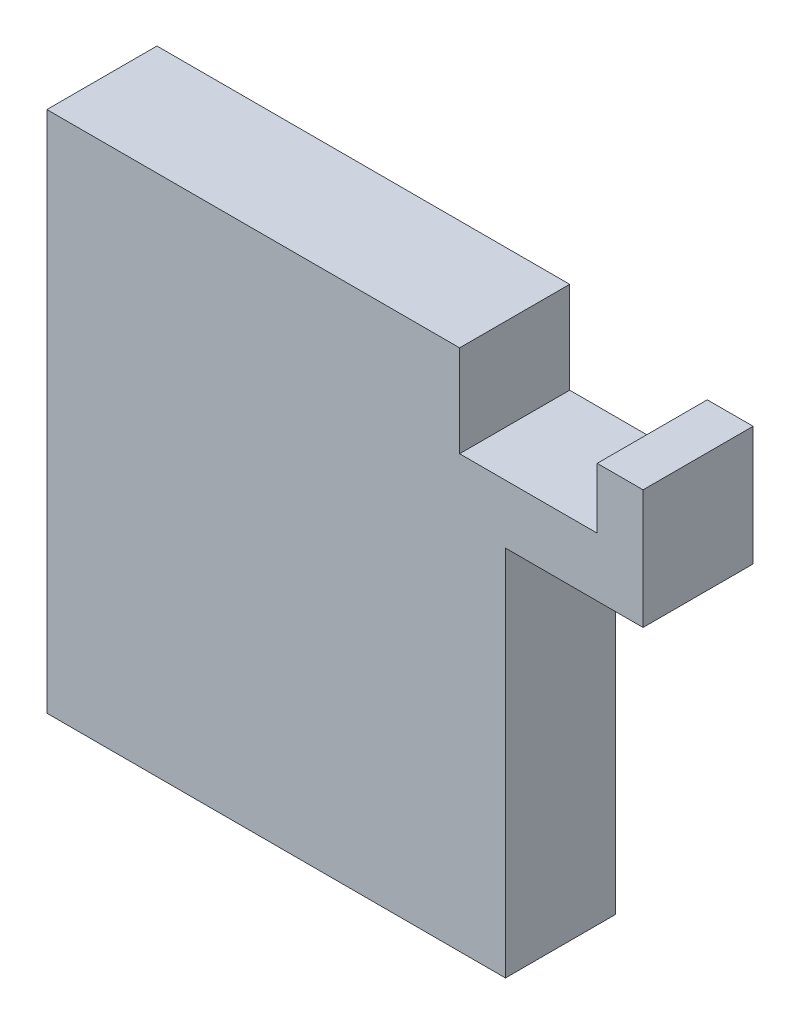
SolidWorks part; units mm, degrees
ref_plane "前视基准面" through (0, 0, 0) normal (0, 0, 1) x (1, 0, 0)
ref_plane "上视基准面" through (0, 0, 0) normal (0, 1, 0) x (1, 0, 0)
ref_plane "右视基准面" through (0, 0, 0) normal (1, 0, 0) x (0, 0, -1)
sketch "草图1" plane through (0, 0, 0) normal (0, 0, 1) x (1, 0, 0)
  line L0 (3.4, 10.5) -> (3.4, 4.8)
  line L1 (3.4, 10.5) -> (7.9, 10.5)
  line L2 (7.9, 10.5) -> (7.9, 9.5)
  line L3 (7.9, 9.5) -> (9.4, 9.5)
  line L4 (9.4, 9.5) -> (9.4, 10.1595)
  line L5 (9.4, 10.1595) -> (9.9, 10.1595)
  line L6 (9.9, 10.1595) -> (9.9, 8.8595)
  line L7 (8.4, 4.8) -> (3.4, 4.8)
  line L9 (9.4, -1.5) -> (9.4, -1) construction
  line L10 (9.9, 8.8595) -> (8.4, 8.8595)
  line L11 (8.4, 8.8595) -> (8.4, 4.8)
  line L12 (9.4, -1) -> (9.1, -1) construction
  line L13 (9.4, 9.5) -> (9.4, 8.8595) construction
  line L14 (10.4, 7.8) -> (-18.1, 7.8) construction
  point P14 (9.25, -1)
  dimension "D1" = 1.3
  dimension "D2" = 0.5
  dimension "D3" = 1.5
  dimension "D4" = 10.5
  dimension "D5" = 5
  dimension "D6" = 1
  dimension "D7" = 3
  dimension "D8" = 1
extrude "凸台-拉伸1" add sketch "草图1" along normal blind 1.2 contours L1 L2 L3 L4 L5 L6 L10 L11 L7 L0
